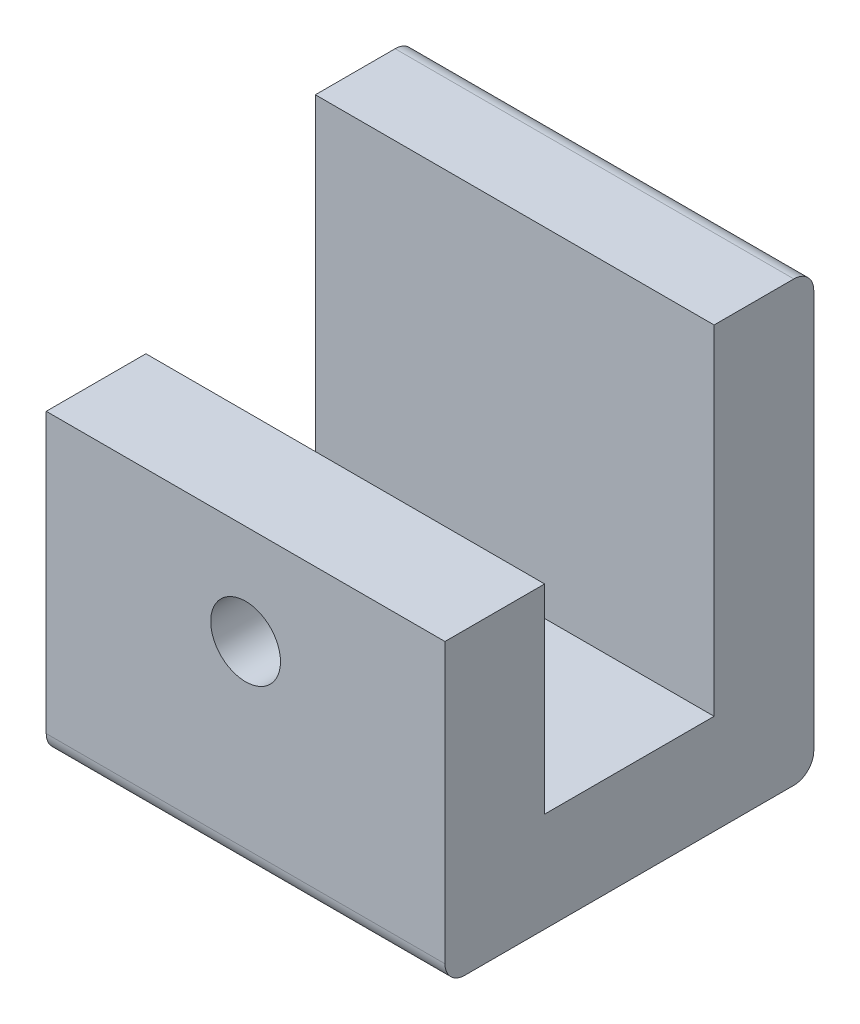
SolidWorks part; units mm, degrees
material "PET"
ref_plane "Piano frontale" through (0, 0, 0) normal (0, 0, 1) x (1, 0, 0)
ref_plane "Piano superiore" through (0, 0, 0) normal (0, 1, 0) x (1, 0, 0)
ref_plane "Piano destro" through (0, 0, 0) normal (1, 0, 0) x (0, 0, -1)
sketch "Schizzo1" plane through (0, 0, 0) normal (0, 0, 1) x (1, 0, 0)
  line L0 (0, -7.5) -> (0, 2.5)
  line L1 (10, 7.5) -> (-10, 7.5)
  line L2 (10, 7.5) -> (10, -7.5)
  line L3 (10, -7.5) -> (-10, -7.5)
  line L4 (-10, 7.5) -> (-10, -7.5)
  line L5 (10, 7.5) -> (-10, -7.5) construction
  line L6 (10, -7.5) -> (-10, 7.5) construction
  circle A0 centre (0, 2.5) radius 1.75
  point P0 (0, 0)
  dimension "D4" = 3.5
  dimension "D1" = 20
  dimension "D2" = 15
  dimension "D3" = 10
extrude "Estrusione-Estrusione1" add sketch "Schizzo1" along normal blind 5
sketch "Schizzo3" plane through (0, 0, 0) normal (0, 0, -1) x (-1, 0, 0)
  line L0 (10, 7.5) -> (10, -7.5) construction
  line L1 (-10, -7.5) -> (10, -7.5)
  line L2 (-10, -7.5) -> (-10, -2.5)
  line L3 (-10, -2.5) -> (10, -2.5)
  line L4 (10, -7.5) -> (10, -2.5)
  dimension "D1" = 5
extrude "Estrusione-Estrusione2" add sketch "Schizzo3" along normal blind 13.5
sketch "Schizzo4" plane through (0, -2.5, 0) normal (0, 1, 0) x (1, 0, 0)
  line L0 (-10, 13.5) -> (-10, 0) construction
  line L1 (10, 13.5) -> (-10, 13.5)
  line L2 (10, 13.5) -> (10, 8.5)
  line L3 (10, 8.5) -> (-10, 8.5)
  line L4 (-10, 13.5) -> (-10, 8.5)
  dimension "D1" = 5
extrude "Estrusione-Estrusione3" add sketch "Schizzo4" along normal blind 17
fillet "Raccordo1" radius 1 3 edges at (0, -7.5, -13.5) (0, -7.5, 5) (0, 14.5, -13.5)
